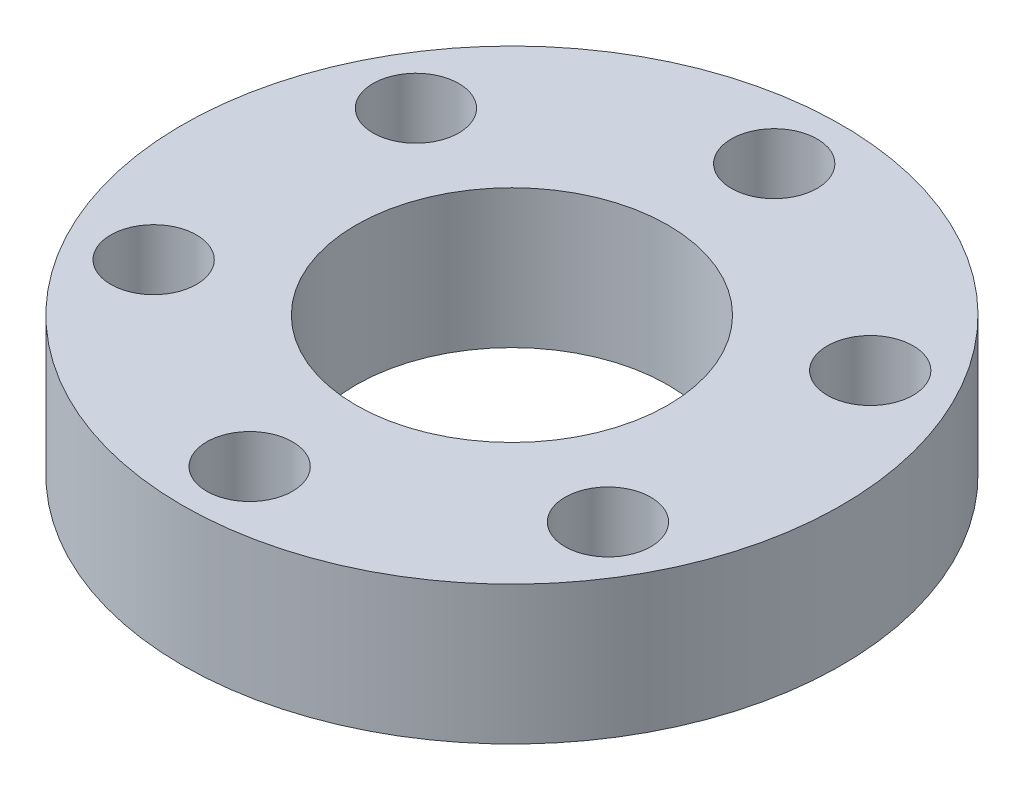
SolidWorks part; units mm, degrees
ref_plane "前视基准面" through (0, 0, 0) normal (0, 0, 1) x (1, 0, 0)
ref_plane "上视基准面" through (0, 0, 0) normal (0, 1, 0) x (1, 0, 0)
ref_plane "右视基准面" through (0, 0, 0) normal (1, 0, 0) x (0, 0, -1)
sketch "草图1" plane through (0, 0, 0) normal (0, 1, 0) x (1, 0, 0)
  circle A0 centre (0, 0) radius 8
  circle A1 centre (0, 0) radius 13.45
  circle A2 centre (0, 0) radius 16.9
  circle A3 centre (0, 13.45) radius 2.2
  circle A4 centre (11.648, 6.725) radius 2.2
  circle A5 centre (11.648, -6.725) radius 2.2
  circle A6 centre (0, -13.45) radius 2.2
  circle A7 centre (-11.648, -6.725) radius 2.2
  circle A8 centre (-11.648, 6.725) radius 2.2
  point P19 (0, 0)
  dimension "D1" = 16
  dimension "D2" = 26.9
  dimension "D3" = 33.8
  dimension "D4" = 4.4
  dimension "D5" = 6
extrude "凸台-拉伸1" add sketch "草图1" along normal blind 7.1 contours A2 A8 A1 A3 A4 A5 A6 A7 | A8 A1 A7 A6 A5 A4 A3 A0
